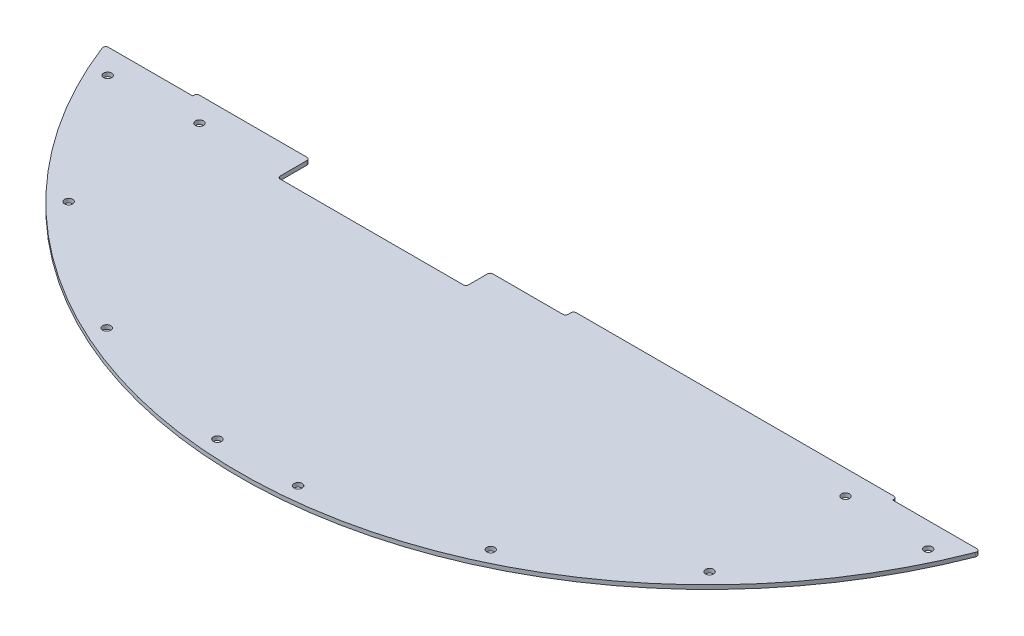
SolidWorks part; units mm, degrees
material "3.3535 (EN-AW 5754)"
ref_plane "Plan de face" through (0, 0, 0) normal (0, 0, 1) x (1, 0, 0)
ref_plane "Plan de dessus" through (0, 0, 0) normal (0, 1, 0) x (1, 0, 0)
ref_plane "Plan de droite" through (0, 0, 0) normal (1, 0, 0) x (0, 0, -1)
sketch "Esquisse1" plane through (0, 0, 0) normal (0, 1, 0) x (1, 0, 0)
  line L0 (0, 0) -> (0, -174) construction
  line L1 (-130, -60) -> (130, -60)
  line L2 (130, -60) -> (130, -61.5)
  line L6 (162.769, -61.5) -> (130, -61.5)
  line L8 (-162.769, -61.5) -> (-130, -61.5)
  line L9 (-130, -60) -> (-130, -61.5)
  circle A0 centre (-120, -69) radius 1.5
  circle A3 centre (120, -69) radius 1.5
  arc A4 (-162.769, -61.5) -> (0, -174) centre (0, 0) ccw
  arc A5 (0, -174) -> (162.769, -61.5) centre (0, 0) ccw
  dimension "D2" = 60
  dimension "D3" = 9
  dimension "D4" = 3
  dimension "D5" = 240
  dimension "D10" = 260
  dimension "D12" = 1.5
  dimension "D6" = 174
extrude "Boss.-Extru.1" add sketch "Esquisse1" along normal blind 1.5
fillet "Congé2" radius 1 4 edges at (-130, 0.75, 60) (-162.769, 0.75, 61.5) (130, 0.75, 60) (162.769, 0.75, 61.5)
sketch "Esquisse2" plane through (0, 1.5, 0) normal (0, 1, 0) x (1, 0, 0)
  circle A0 centre (-15, -167.329) radius 1.5
  arc A19 (-162.2481, -62.8613) -> (162.2481, -62.8613) centre (0, 0) ccw construction
  circle A25 centre (0, 0) radius 168 construction
  dimension "D1" = 15
  dimension "D2" = 6
  dimension "D3" = 3
  dimension "D5" = 168
extrude "Enlèv. mat.-Extru.1" cut sketch "Esquisse2" against normal through all
pattern_circular "Répétition circulaire1" count 4 every 20 about axis through (0, 0, 0) along (0, 1, 0) of "Enlèv. mat.-Extru.1"
mirror "Symétrie1" about plane through (0, 0, 0) normal (1, 0, 0) of "Répétition circulaire1", "Enlèv. mat.-Extru.1"
sketch "Esquisse3" plane through (0, 1.5, 0) normal (0, 1, 0) x (1, 0, 0)
  line L0 (129, -60) -> (-129, -60) construction
  line L1 (-88, -60) -> (10, -60)
  line L2 (-88, -60) -> (-88, -72)
  line L3 (-88, -72) -> (-18, -72)
  line L4 (10, -60) -> (10, -63)
  line L8 (10, -63) -> (-18, -63)
  line L9 (-18, -72) -> (-18, -63)
  point P1 (-53, -72)
  dimension "D1" = 10
  dimension "D2" = 3
  dimension "D3" = 12
  dimension "D4" = 53
  dimension "D5" = 70
extrude "Enlèv. mat.-Extru.2" cut sketch "Esquisse3" against normal through all
fillet "Congé3" radius 1 6 edges at (10, 0.75, 60) (10, 0.75, 63) (-18, 0.75, 63) (-18, 0.75, 72) (-88, 0.75, 72) (-88, 0.75, 60)
